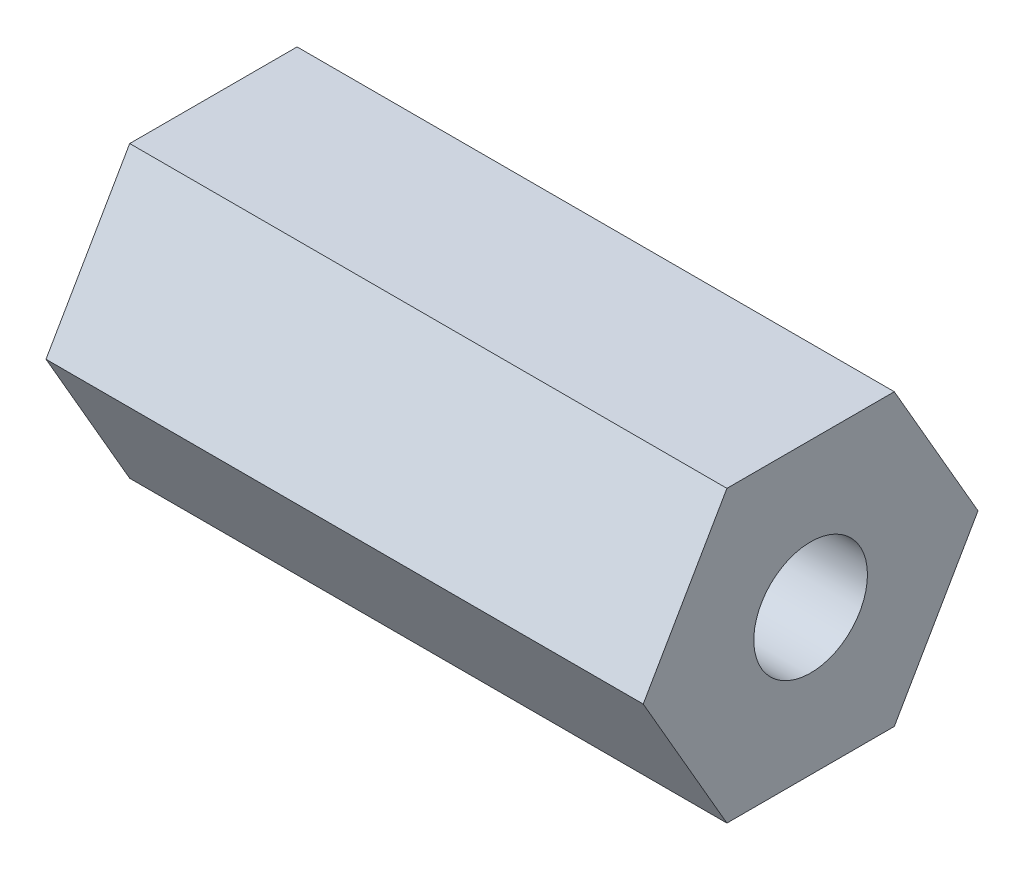
SolidWorks part; units mm, degrees
material "6061 Alloy"
ref_plane "Front Plane" through (0, 0, 0) normal (0, 0, 1) x (1, 0, 0)
ref_plane "Top Plane" through (0, 0, 0) normal (0, 1, 0) x (1, 0, 0)
ref_plane "Right Plane" through (0, 0, 0) normal (1, 0, 0) x (0, 0, -1)
sketch "Sketch1" plane through (0, 0, 0) normal (1, 0, 0) x (0, 0, -1)
  line L1 (7.3323, 0) -> (3.6662, 6.35)
  line L2 (3.6662, 6.35) -> (-3.6662, 6.35)
  line L3 (-3.6662, 6.35) -> (-7.3323, 0)
  line L4 (-7.3323, 0) -> (-3.6662, -6.35)
  line L5 (-3.6662, -6.35) -> (3.6662, -6.35)
  line L6 (3.6662, -6.35) -> (7.3323, 0)
  circle A0 centre (0, 0) radius 6.35 construction
  circle A1 centre (0, 0) radius 2.4892
  dimension "D1" = 12.7
  dimension "D2" = 4.9784
extrude "Boss-Extrude1" add sketch "Sketch1" along normal blind 26.162
